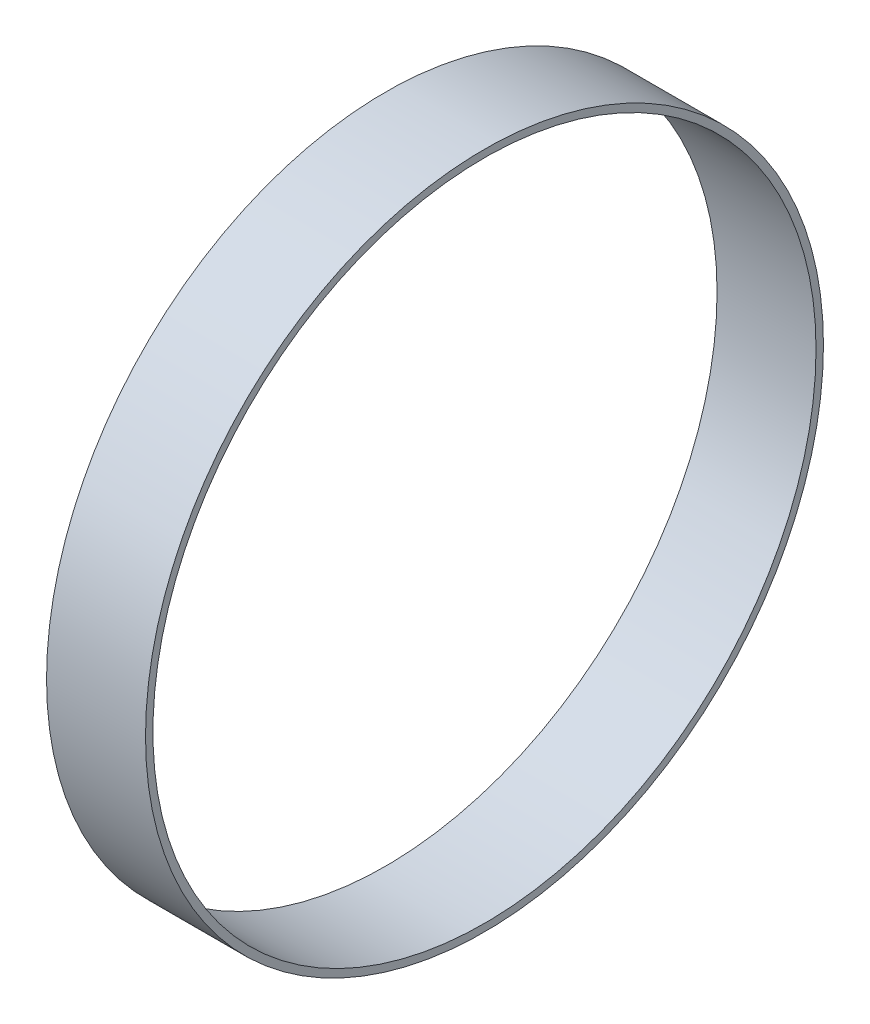
SolidWorks part; units mm, degrees
ref_plane "Front Plane" through (0, 0, 0) normal (1, 0, 0) x (0, 1, 0)
ref_plane "Top Plane" through (0, 0, 0) normal (0, 0, 1) x (0, 1, 0)
ref_plane "Right Plane" through (0, 0, 0) normal (0, 1, 0) x (-1, 0, 0)
sketch "Sketch1" plane through (0, 0, 0) normal (1, 0, 0) x (0, 1, 0)
  circle A0 centre (0, 0) radius 86.995
  circle A1 centre (0, 0) radius 85.09
  dimension "D1" = 173.99
  dimension "D2" = 170.18
extrude "Boss-Extrude1" add sketch "Sketch1" along normal blind 25.4
